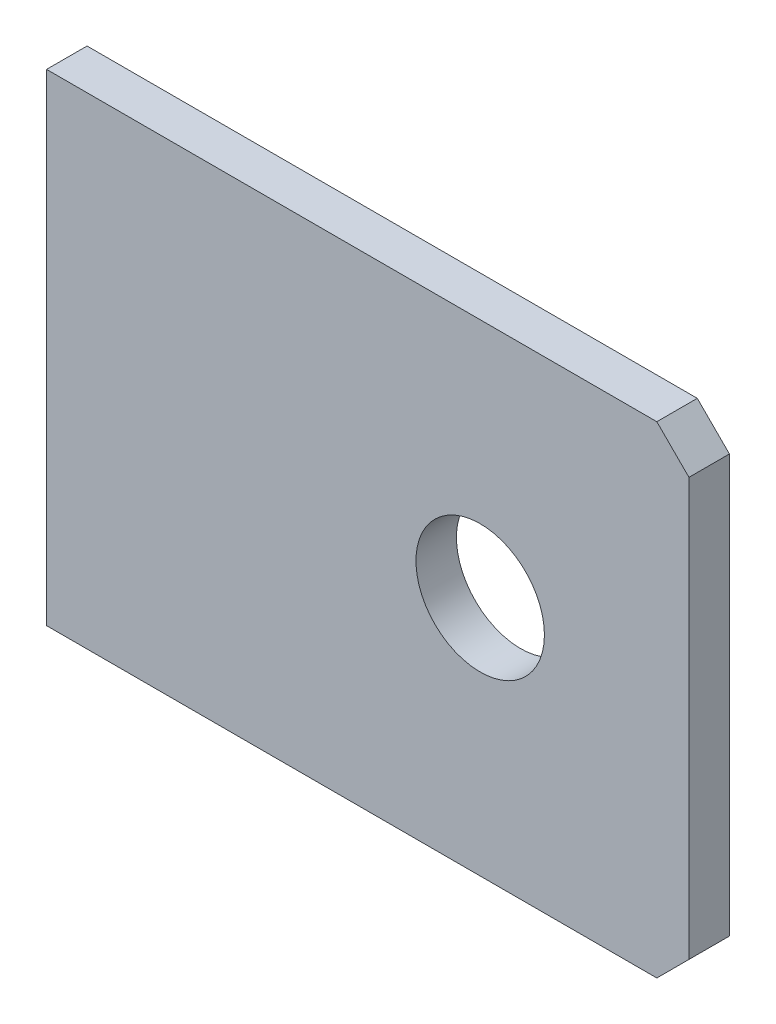
SolidWorks part; units mm, degrees
ref_plane "Plano frontal" through (0, 0, 0) normal (0, 0, 1) x (1, 0, 0)
ref_plane "Plano superior" through (0, 0, 0) normal (0, 1, 0) x (1, 0, 0)
ref_plane "Plano direito" through (0, 0, 0) normal (1, 0, 0) x (0, 0, -1)
sketch "Esboço1" plane through (0, 0, 0) normal (0, 0, 1) x (1, 0, 0)
  line L0 (10, -6.5) -> (10, 6.5)
  line L1 (10, 6.5) -> (9, 7.5)
  line L2 (9, 7.5) -> (-10, 7.5)
  line L3 (-10, 7.5) -> (-10, -7.5)
  line L4 (-10, -7.5) -> (9, -7.5)
  line L5 (9, -7.5) -> (10, -6.5)
  circle A0 centre (3.5, 0) radius 2
extrude "Ressalto-extrusão1" add sketch "Esboço1" along normal blind 1.26
